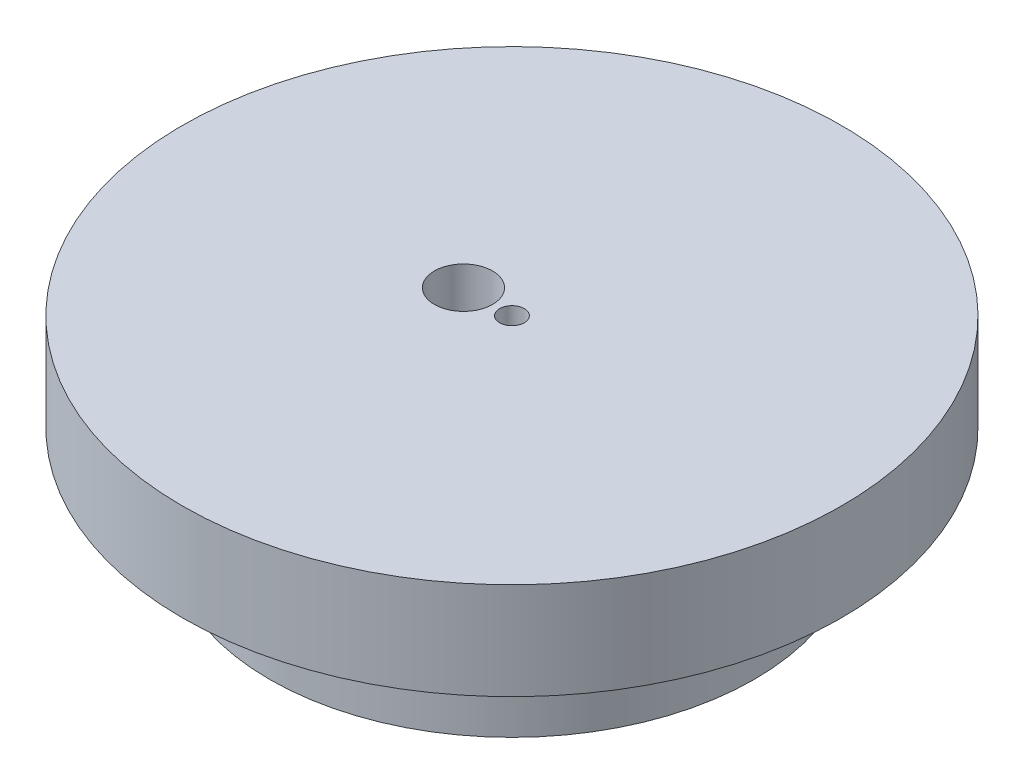
SolidWorks part; units mm, degrees
ref_plane "Front Plane" through (0, 0, 0) normal (0, 0, 1) x (1, 0, 0)
ref_plane "Top Plane" through (0, 0, 0) normal (0, 1, 0) x (1, 0, 0)
ref_plane "Right Plane" through (0, 0, 0) normal (1, 0, 0) x (0, 0, -1)
sketch "Sketch1" plane through (0, 0, 0) normal (0, 1, 0) x (1, 0, 0)
  line L39 (0, 8.5) -> (0, 11) construction
  line L40 (-1.5, 11) -> (1.5, 11)
  line L41 (-1.5, 11) -> (-2.4259, 8.1465)
  line L42 (1.5, 11) -> (2.4259, 8.1465)
  line L43 (6.7175, 8.8388) -> (4.045, 7.4758)
  line L44 (6.7175, 8.8388) -> (8.8388, 6.7175)
  line L45 (8.8388, 6.7175) -> (7.4758, 4.045)
  line L46 (11, 1.5) -> (8.1465, 2.4259)
  line L47 (11, 1.5) -> (11, -1.5)
  line L48 (11, -1.5) -> (8.1465, -2.4259)
  line L49 (8.8388, -6.7175) -> (7.4758, -4.045)
  line L50 (8.8388, -6.7175) -> (6.7175, -8.8388)
  line L51 (6.7175, -8.8388) -> (4.045, -7.4758)
  line L52 (1.5, -11) -> (2.4259, -8.1465)
  line L53 (1.5, -11) -> (-1.5, -11)
  line L54 (-1.5, -11) -> (-2.4259, -8.1465)
  line L55 (-6.7175, -8.8388) -> (-4.045, -7.4758)
  line L56 (-6.7175, -8.8388) -> (-8.8388, -6.7175)
  line L57 (-8.8388, -6.7175) -> (-7.4758, -4.045)
  line L58 (-11, -1.5) -> (-8.1465, -2.4259)
  line L59 (-11, -1.5) -> (-11, 1.5)
  line L60 (-11, 1.5) -> (-8.1465, 2.4259)
  line L61 (-8.8388, 6.7175) -> (-7.4758, 4.045)
  line L62 (-8.8388, 6.7175) -> (-6.7175, 8.8388)
  line L63 (-6.7175, 8.8388) -> (-4.045, 7.4758)
  circle A14 centre (0, 0) radius 8.5 construction
  arc A15 (2.4259, 8.1465) -> (4.045, 7.4758) centre (0, 0) cw
  arc A16 (7.4758, 4.045) -> (8.1465, 2.4259) centre (0, 0) cw
  arc A17 (8.1465, -2.4259) -> (7.4758, -4.045) centre (0, 0) cw
  arc A18 (4.045, -7.4758) -> (2.4259, -8.1465) centre (0, 0) cw
  arc A19 (-2.4259, -8.1465) -> (-4.045, -7.4758) centre (0, 0) cw
  arc A20 (-7.4758, -4.045) -> (-8.1465, -2.4259) centre (0, 0) cw
  arc A21 (-8.1465, 2.4259) -> (-7.4758, 4.045) centre (0, 0) cw
  arc A22 (-4.045, 7.4758) -> (-2.4259, 8.1465) centre (0, 0) cw
  circle A23 centre (0, 0) radius 25
  point P31 (0, 0)
  point P71 (0, 11)
  point P105 (0, 0)
  dimension "D1" = 50
  dimension "D5" = 17
  dimension "D6" = 2.5
  dimension "D7" = 3
  dimension "D8" = 3
  dimension "D9" = 8
extrude "Boss-Extrude1" add sketch "Sketch1" along normal blind 10
sketch "Sketch2" plane through (0, 10, 0) normal (0, 1, 0) x (1, 0, 0)
  circle A0 centre (0, 0) radius 1.27
  circle A1 centre (0, 0) radius 34
  dimension "D1" = 2.54
  dimension "D2" = 68
extrude "Boss-Extrude2" add sketch "Sketch2" along normal blind 10
sketch "Sketch3" plane through (0, 20, 0) normal (0, 1, 0) x (1, 0, 0)
  circle A0 centre (-5, 0) radius 3
  dimension "D2" = 6
  dimension "D1" = 5
extrude "Cut-Extrude1" cut sketch "Sketch3" against normal through all
